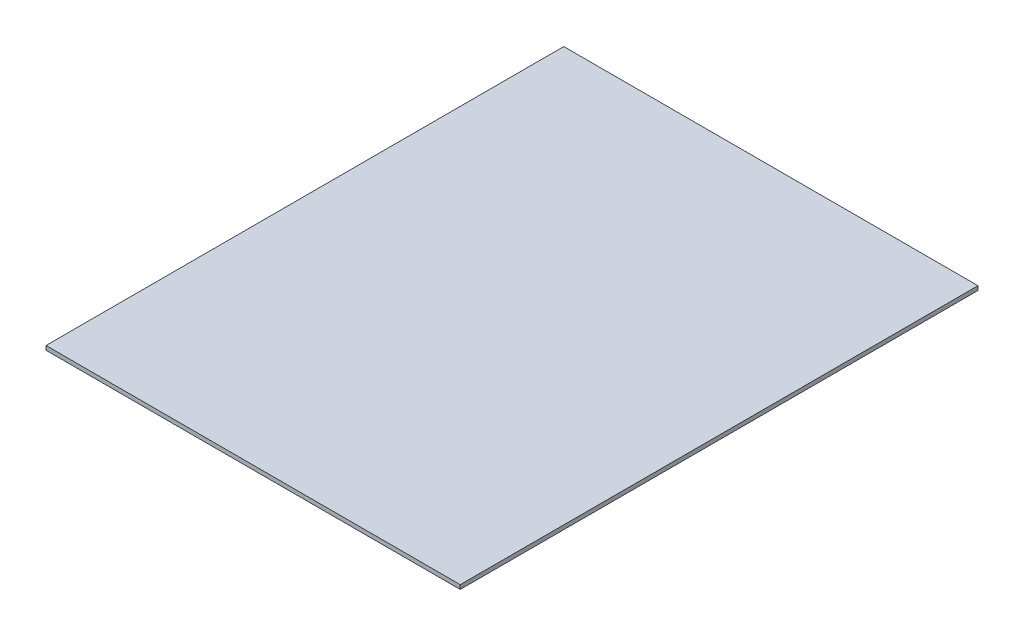
SolidWorks part; units mm, degrees
ref_plane "Front Plane" through (0, 0, 0) normal (0, 0, 1) x (1, 0, 0)
ref_plane "Top Plane" through (0, 0, 0) normal (0, 1, 0) x (1, 0, 0)
ref_plane "Right Plane" through (0, 0, 0) normal (1, 0, 0) x (0, 0, -1)
other "Configuration Table"
sketch "Sketch1" plane through (0, 0, 0) normal (0, 0, 1) x (1, 0, 0)
  line L1 (150, 1446) -> (550, 1446)
  line L2 (150, 1446) -> (150, 1450)
  line L3 (150, 1450) -> (550, 1450)
  line L4 (550, 1446) -> (550, 1450)
extrude "OVEN_OMAKE_hazne_2_tepsi_duzlemi_145_1" add sketch "Sketch1" against normal blind 500 from offset 60 separate body
